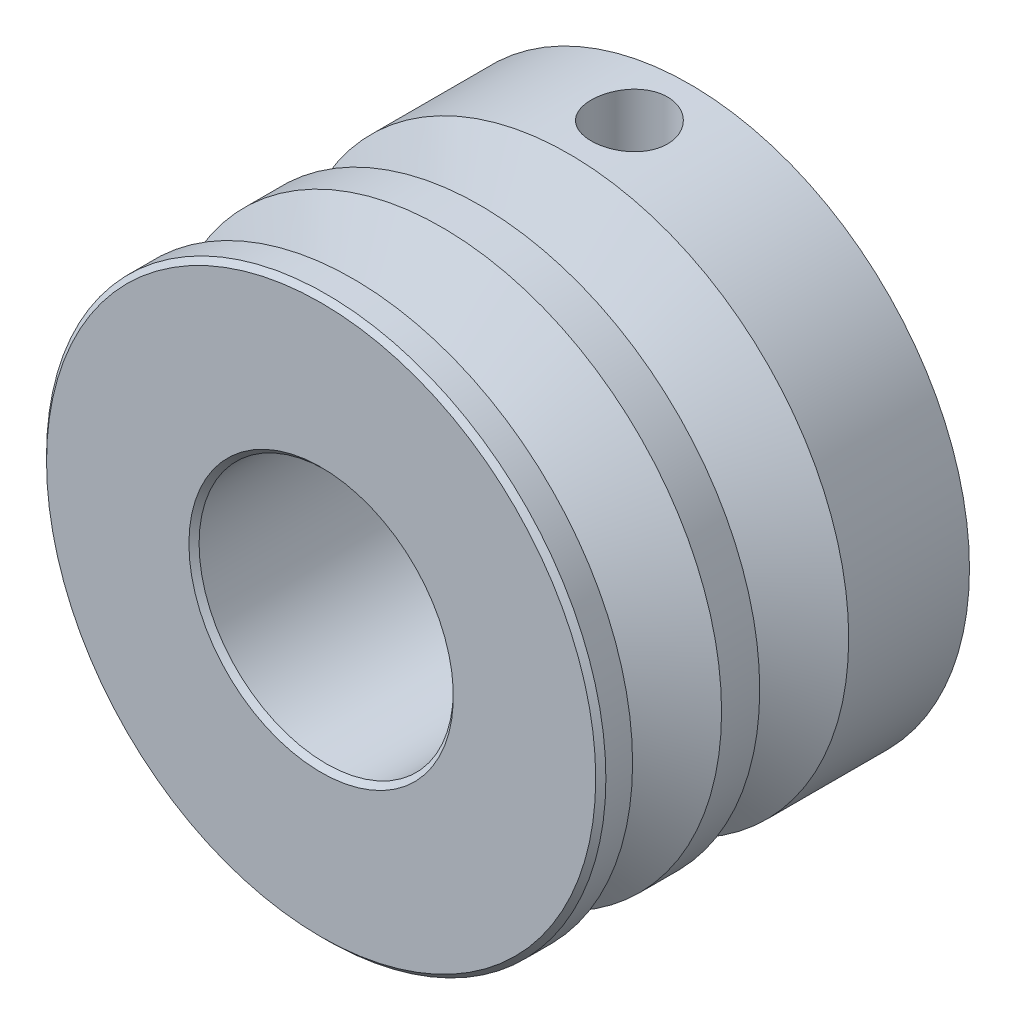
SolidWorks part; units mm, degrees
ref_plane "前视基准面" through (0, 0, 0) normal (0, 0, 1) x (1, 0, 0)
ref_plane "上视基准面" through (0, 0, 0) normal (0, 1, 0) x (1, 0, 0)
ref_plane "右视基准面" through (0, 0, 0) normal (1, 0, 0) x (0, 0, -1)
sketch "草图1" plane through (0, 0, 0) normal (1, 0, 0) x (0, 0, -1)
  line L0 (0, 0) -> (46.9269, 0) construction
  line L1 (0, 5) -> (15, 5)
  line L2 (0, 11) -> (1.25, 11)
  line L3 (1.25, 11) -> (2.9134, 8.1189)
  line L4 (3.0866, 8.1189) -> (4.75, 11)
  line L5 (4.75, 11) -> (6.25, 11)
  line L6 (6.25, 11) -> (7.9134, 8.1189)
  line L7 (8.0866, 8.1189) -> (9.75, 11)
  line L8 (9.75, 11) -> (14.5, 11)
  line L9 (15, 6) -> (15, 5)
  line L10 (0, 11) -> (0, 5)
  line L11 (14.5, 11) -> (14.5, 6)
  line L12 (14.5, 6) -> (15, 6)
  arc A0 (3.0866, 8.1189) -> (2.9134, 8.1189) centre (3, 8.1689) cw
  arc A1 (8.0866, 8.1189) -> (7.9134, 8.1189) centre (8, 8.1689) cw
  point P17 (3, 7.9689)
  point P20 (8, 7.9689)
  dimension "D13" = 0.1
  dimension "D1" = 5
  dimension "D2" = 6
  dimension "D3" = 3
  dimension "D4" = 1.25
  dimension "D5" = 3.5
  dimension "D6" = 5
  dimension "D7" = 60
  dimension "D8" = 3.5
  dimension "D9" = 15
  dimension "D10" = 0.5
  dimension "D11" = 6
revolve "旋转1" add sketch "草图1" angle 360 about L0
hole_wizard "M3 螺纹孔1" positions "草图3" profile "草图2" tap size "M3" standard "GB"
sketch "草图3" plane through (0, 0, 0) normal (0, 1, 0) x (1, 0, 0)
  line L0 (11, 14.5) -> (-11, 14.5) construction
  point P0 (0, 12.125)
  dimension "D1" = 2.375
sketch "草图2" plane through (0, 0, -12.125) normal (1, 0, 0) x (0, 0, -1)
  line L0 (0, 0) -> (0, 15.0263)
  line L1 (0, 15.0263) -> (1.5, 15.0263)
  line L2 (1.5, 15.0263) -> (1.5, 0)
  line L5 (1.5, 0) -> (0, 0)
  line L11 (0, -6.35) -> (0, 107.95) construction
  dimension "螺纹线主直径" = 3
  dimension "通孔螺纹孔钻头深度" = 15.0263
pattern_circular "阵列(圆周)1" count 2 every 120 about axis through (0, 0, 0) along (0, 0, 1) of "M3 螺纹孔1"
chamfer "倒角1" distance 0.2 angle 45 4 edges at (11, 0, 0) (5, 0, 0) (5, 0, -15) (6, 0, -15)
